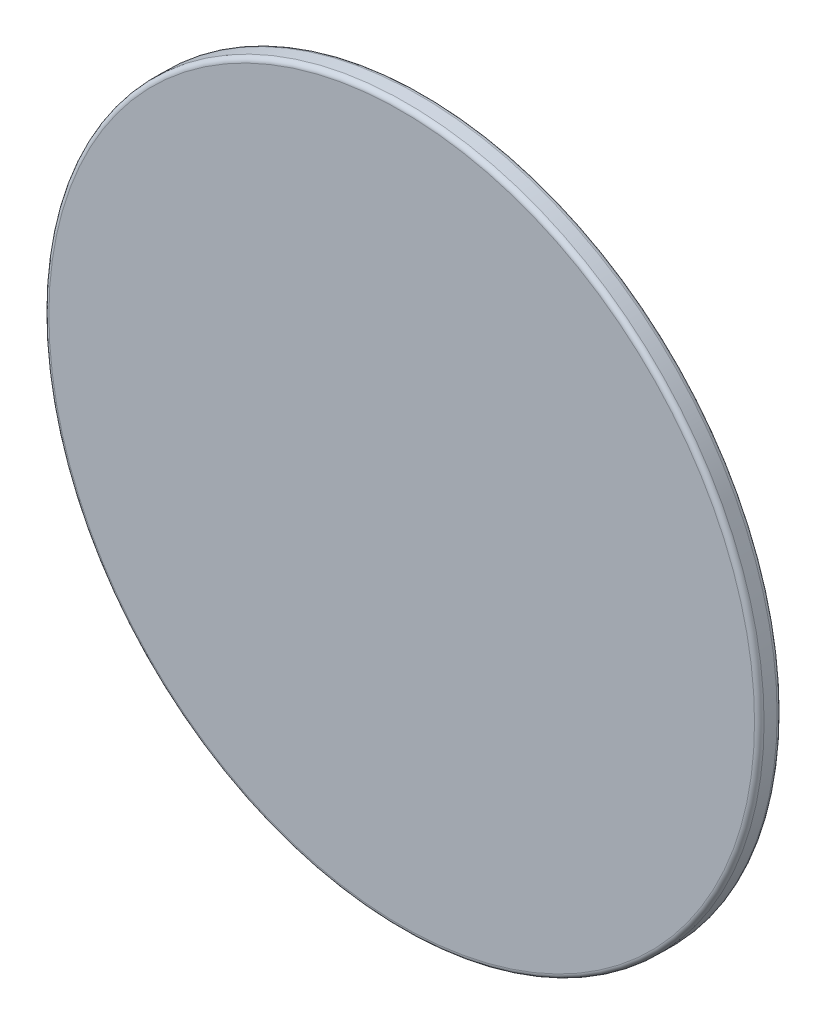
SolidWorks part; units mm, degrees
ref_plane "Front Plane" through (0, 0, 0) normal (0, 0, 1) x (1, 0, 0)
ref_plane "Top Plane" through (0, 0, 0) normal (0, 1, 0) x (1, 0, 0)
ref_plane "Right Plane" through (0, 0, 0) normal (1, 0, 0) x (0, 0, -1)
sketch "Sketch1" plane through (0, 0, 0) normal (0, 0, 1) x (1, 0, 0)
  circle A0 centre (0, 0) radius 19
  dimension "D1" = 38
extrude "Boss-Extrude1" add sketch "Sketch1" along normal blind 1.2
fillet "Fillet1" radius 0.254 2 edges at (19, 0, 0) (19, 0, 1.2)
